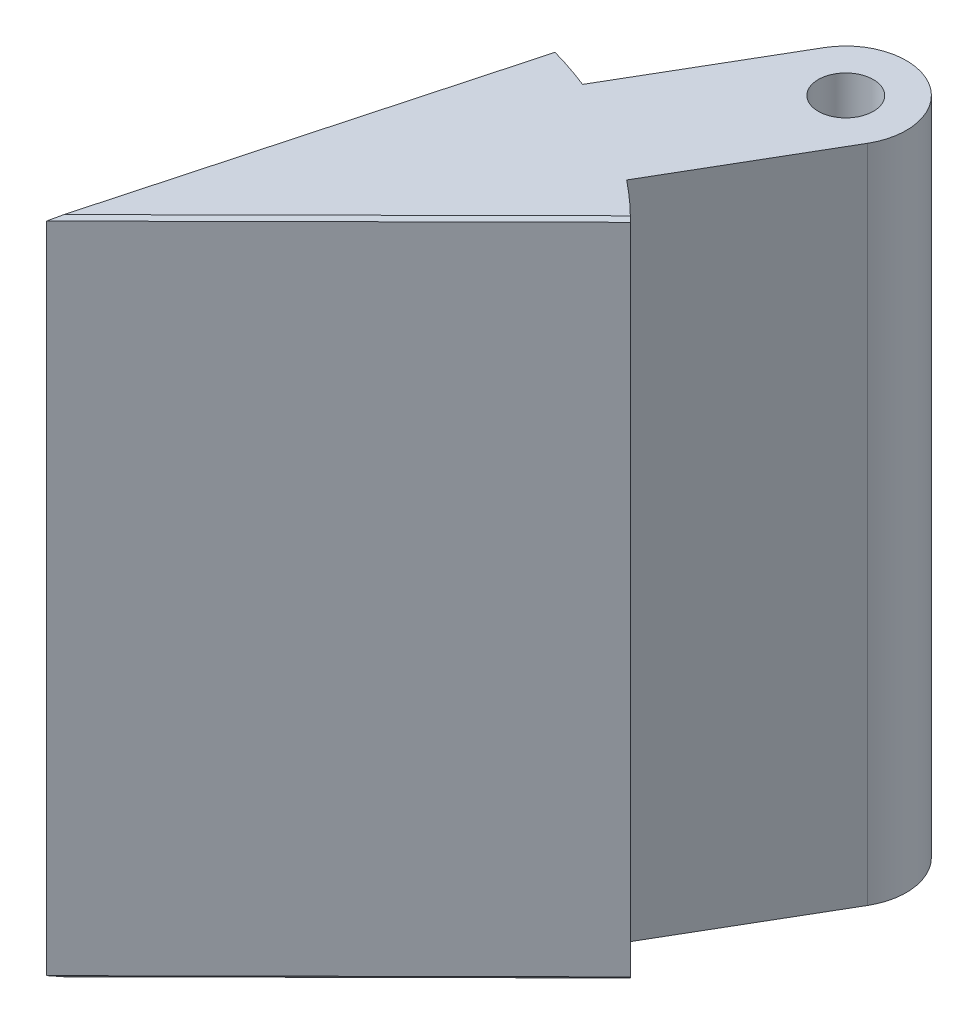
SolidWorks part; units mm, degrees
material "Plain Carbon Steel"
ref_plane "Front Plane" through (0, 0, 0) normal (0, 0, 1) x (1, 0, 0)
ref_plane "Top Plane" through (0, 0, 0) normal (0, 1, 0) x (1, 0, 0)
ref_plane "Right Plane" through (0, 0, 0) normal (1, 0, 0) x (0, 0, -1)
sketch "Sketch1" plane through (0, 0, 0) normal (0, 1, 0) x (1, 0, 0)
  line L0 (-7.6575, 8.45) -> (-7.7242, -9.2583) construction
  line L1 (-7.6992, -9.2333) -> (-7.7117, -9.2367) construction
  line L2 (-7.7117, -9.2367) -> (-7.7208, -9.2458) construction
  line L3 (-7.7208, -9.2458) -> (-7.7242, -9.2583) construction
  line L4 (-7.7242, -9.2583) -> (-7.7208, -9.2708) construction
  line L5 (-7.7208, -9.2708) -> (-7.7117, -9.28) construction
  line L6 (-7.7117, -9.28) -> (-7.6992, -9.2833) construction
  line L7 (-7.6992, -9.2833) -> (-7.6867, -9.28) construction
  line L8 (-7.6867, -9.28) -> (-7.6775, -9.2708) construction
  line L9 (-7.6775, -9.2708) -> (-7.6742, -9.2583) construction
  line L10 (-7.6742, -9.2583) -> (-7.6775, -9.2458) construction
  line L11 (-7.6775, -9.2458) -> (-7.6867, -9.2367) construction
  line L12 (-7.6867, -9.2367) -> (-7.6992, -9.2333) construction
  line L13 (2.7768, 5.1332) -> (0.1424, 0.6098)
  line L14 (-7.7242, -9.2583) -> (-7.7208, -9.2458)
  line L15 (7.6575, -0.4403) -> (-7.7117, -9.2367) construction
  line L16 (0.1424, 0.6098) -> (0.0893, 0.5186)
  line L17 (-7.7208, -9.2458) -> (-4.4418, 2.8098)
  line L18 (-7.7208, -9.2458) -> (1.1558, -0.4357)
  line L19 (-0.3946, 6.9802) -> (-3.0307, 2.4538)
  line L20 (-3.0307, 2.4538) -> (-3.0858, 2.3592)
  line L21 (-7.7202, -9.2448) -> (-7.7208, -9.2458) construction
  circle A0 centre (-7.6992, -9.2583) radius 0.025 construction
  circle A1 centre (-7.6992, -9.2583) radius 0.0241 construction
  circle A2 centre (-7.6575, 8.45) radius 0.8333 construction
  arc A3 (1.9126, 5.6365) -> (0.4695, 6.4769) centre (1.1911, 6.0567) ccw
  circle A4 centre (7.6575, -0.4403) radius 0.8333 construction
  arc A5 (-3.0858, 2.3592) -> (-4.4418, 2.8098) centre (-7.6992, -9.2583) ccw
  arc A6 (2.7768, 5.1332) -> (-0.3946, 6.9802) centre (1.1911, 6.0567) ccw
  circle A7 centre (1.1911, 6.0567) radius 0.835
  arc A8 (1.1558, -0.4357) -> (0.0893, 0.5186) centre (-7.6992, -9.2583) ccw
extrude "Boss-Extrude1" add sketch "Sketch1" along normal blind 20 contours L18 A8 L16 L13 A6 L19 L20 A5 L17 A7 A3
chamfer "Chamfer1" distance 0.1 angle 45 4 edges at (-6.0813, 0, 3.218) (-3.2825, 0, 4.8407) (-6.0813, 20, 3.218) (-3.2825, 20, 4.8407)
